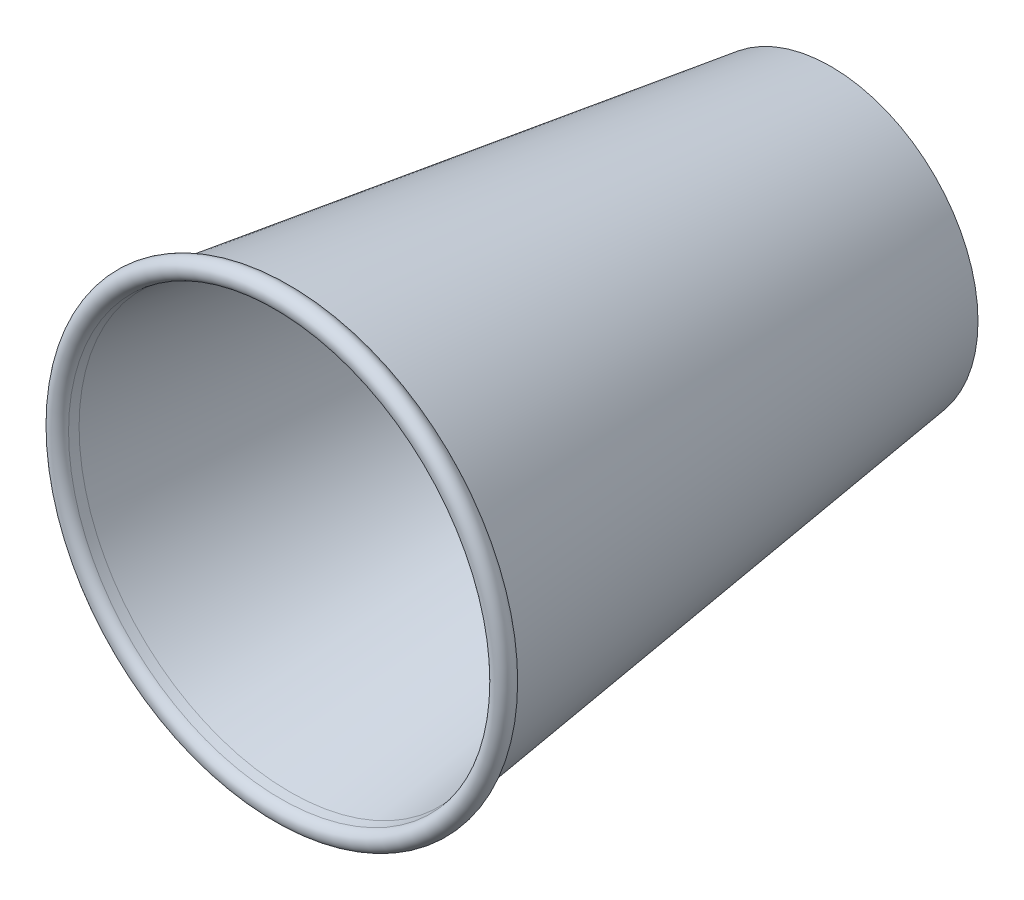
SolidWorks part; units mm, degrees
ref_plane "Front Plane" through (0, 0, 0) normal (1, 0, 0) x (0, 1, 0)
ref_plane "Top Plane" through (0, 0, 0) normal (0, 0, 1) x (0, 1, 0)
ref_plane "Right Plane" through (0, 0, 0) normal (0, 1, 0) x (-1, 0, 0)
sketch "Sketch1" plane through (0, 0, 0) normal (0, 1, 0) x (-1, 0, 0)
  line L0 (0, 3) -> (-27.6, 3)
  line L1 (-27.6, 3) -> (-27.6, 0)
  line L2 (-27.6, 0) -> (-29.573, 0)
  line L3 (-29.573, 0) -> (-44.6161, 110.4)
  line L4 (-44.6161, 110.4) -> (-42.6354, 110.4)
  line L5 (-42.6354, 110.4) -> (-28.2304, 5)
  line L6 (-28.2304, 5) -> (0, 5)
  line L7 (0, 5) -> (0, 3)
  line L8 (0, -50) -> (0, 150) construction
revolve "Cup" add sketch "Sketch1" angle 360 about L8
sketch "Sketch2" plane through (0, 0, 0) normal (0, 1, 0) x (-1, 0, 0)
  line L0 (0, -50) -> (0, 150) construction
  circle A0 centre (-44.6161, 110.4) radius 1.9807
  point P4 (-44.6161, 110.4)
revolve "BeadRound" add sketch "Sketch2" angle 360 about L0
sketch "Sketch3" plane through (0, 0, 0) normal (0, 1, 0) x (-1, 0, 0)
  line L0 (-44.3436, 108.4) -> (-47, 110)
  line L1 (-47, 110) -> (-45.8, 112.4)
  line L2 (-45.8, 112.4) -> (-42.5, 111.6)
  line L3 (-42.5, 111.6) -> (-42.45, 110)
  line L4 (-42.45, 110) -> (-44.3436, 108.4)
  line L5 (0, -50) -> (0, 150) construction
revolve "BeadCollision" [suppressed] add sketch "Sketch3" angle 360 about L5
fillet "Fillet2" radius 100 1 edges at (-42.6354, 0, 110.4)
